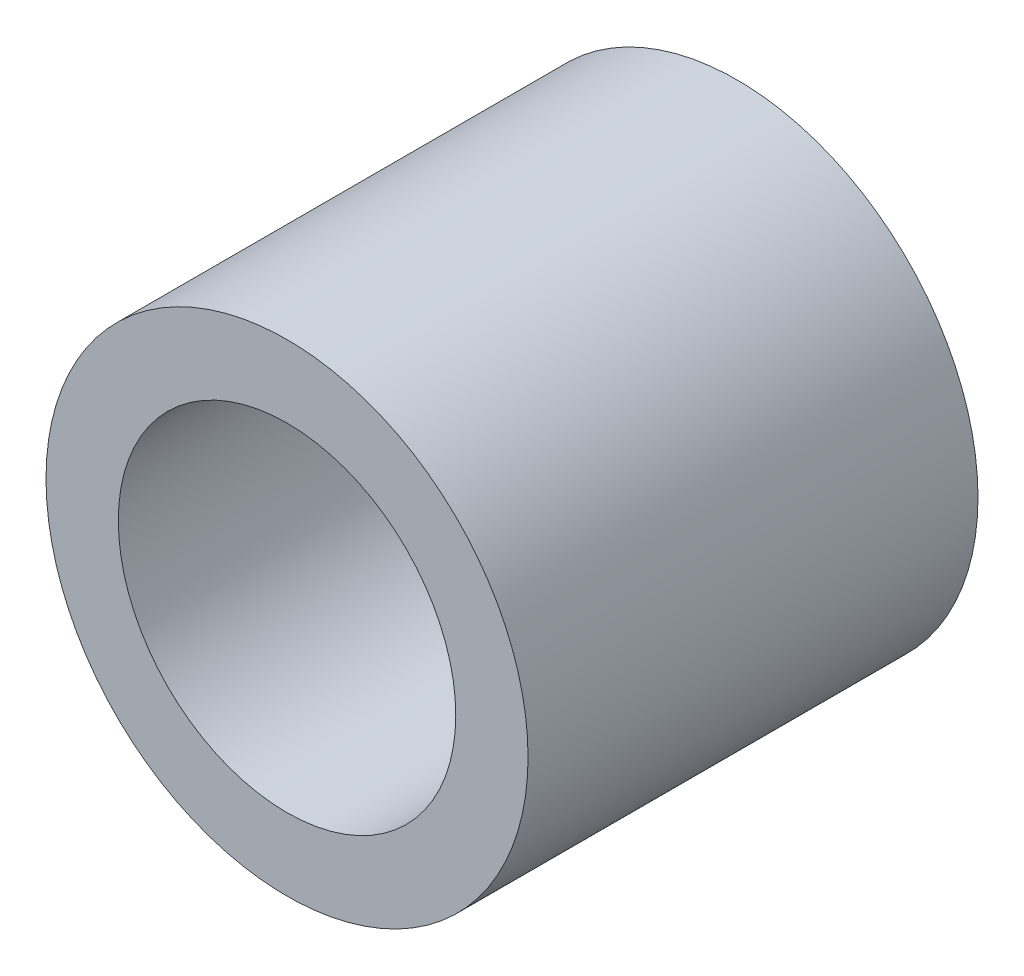
SolidWorks part; units mm, degrees
material "AISI 1020"
ref_plane "Plano frontal" through (0, 0, 0) normal (0, 0, 1) x (1, 0, 0)
ref_plane "Plano superior" through (0, 0, 0) normal (0, 1, 0) x (1, 0, 0)
ref_plane "Plano direito" through (0, 0, 0) normal (1, 0, 0) x (0, 0, -1)
sketch "Esboço1" plane through (0, 0, 0) normal (0, 0, 1) x (1, 0, 0)
  circle A0 centre (0, 0) radius 7.5
  circle A1 centre (0, 0) radius 5.25
  dimension "D1" = 10.5
  dimension "D2" = 15
extrude "Extrusão1" add sketch "Esboço1" along normal mid plane 14
